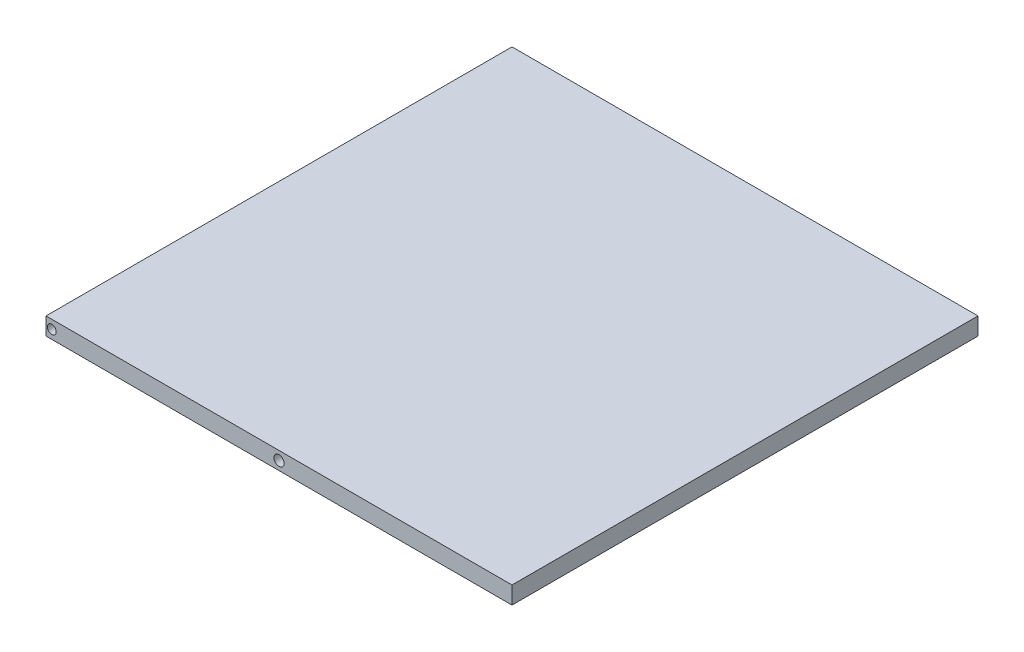
SolidWorks part; units mm, degrees
ref_plane "Front Plane" through (0, 0, 0) normal (0, 0, 1) x (1, 0, 0)
ref_plane "Top Plane" through (0, 0, 0) normal (0, 1, 0) x (1, 0, 0)
ref_plane "Right Plane" through (0, 0, 0) normal (1, 0, 0) x (0, 0, -1)
sketch "Sketch2" plane through (0, 0, 0) normal (0, 1, 0) x (1, 0, 0)
  line L1 (0, 0) -> (-508, 0)
  line L2 (0, 0) -> (0, 508)
  line L3 (0, 508) -> (-508, 508)
  line L4 (-508, 0) -> (-508, 508)
  dimension "D1" = 508
  dimension "D2" = 508
extrude "Boss-Extrude1" add sketch "Sketch2" along normal blind 19.05 contours L1 L4 L3 L2
sketch "Sketch3" plane through (0, 0, 0) normal (0, 0, 1) x (1, 0, 0)
  line L0 (0, 0) -> (-508, 0) construction
  circle A0 centre (-254, 9.525) radius 5.5239
  circle A1 centre (-501.65, 9.525) radius 4.826
  dimension "D3" = 9.652
  dimension "D1" = 254
  dimension "D2" = 9.525
  dimension "D4" = 247.65
sketch "Sketch4" plane through (0, 0, 0) normal (0, 0, 1) x (1, 0, 0)
  circle A1 centre (-501.65, 9.525) radius 5.08
  dimension "D1" = 10.16
  dimension "D2" = 247.65
extrude "Cut-Extrude1" cut sketch "Sketch3" against normal through all
